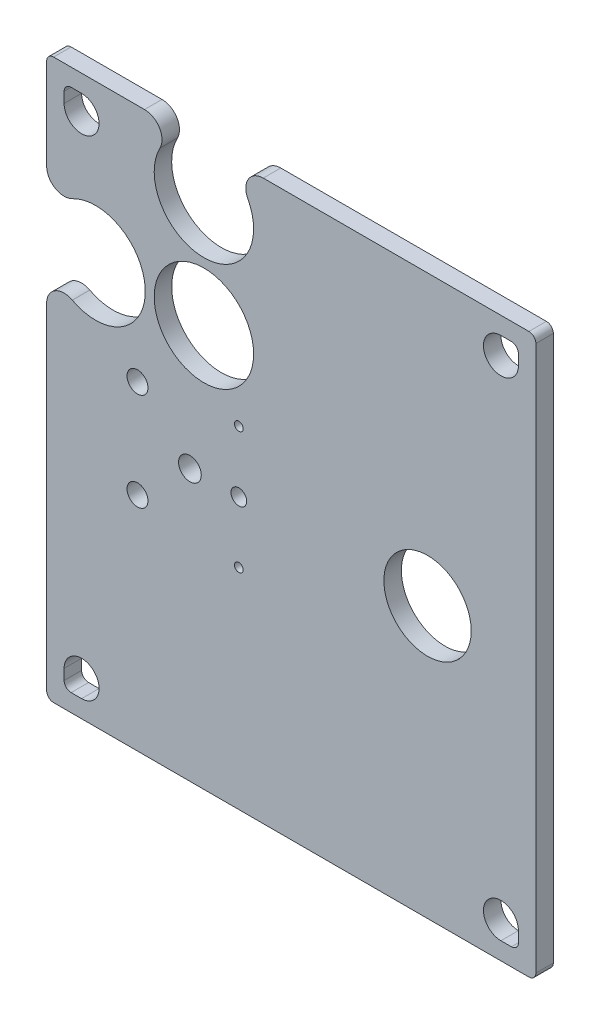
SolidWorks part; units mm, degrees
ref_plane "Front Plane" through (0, 0, 0) normal (0, 0, 1) x (1, 0, 0)
ref_plane "Top Plane" through (0, 0, 0) normal (0, 1, 0) x (1, 0, 0)
ref_plane "Right Plane" through (0, 0, 0) normal (1, 0, 0) x (0, 0, -1)
sketch "Model" plane through (0, 0, 0) normal (0, 0, 1) x (1, 0, 0)
  line L2 (5, 153) -> (5, 150)
  line L3 (10, 155) -> (7, 155)
  line L4 (7, 5) -> (10, 5)
  line L5 (5, 10) -> (5, 7)
  line L6 (135, 7) -> (135, 10)
  line L7 (130, 5) -> (133, 5)
  line L8 (133, 155) -> (130, 155)
  line L9 (135, 150) -> (135, 153)
  line L12 (28.0118, 160) -> (2, 160)
  line L13 (140, 2) -> (140, 158)
  line L14 (2, 0) -> (138, 0)
  line L15 (0, 98.0118) -> (0, 2)
  line L16 (138, 160) -> (61.9882, 160)
  line L17 (0, 158) -> (0, 131.9882)
  circle A0 centre (26, 91.5) radius 3
  circle A1 centre (55, 77.5) radius 2.25
  circle A2 centre (55, 60) radius 1.25
  circle A3 centre (109, 77.5) radius 12.5
  circle A4 centre (55, 95) radius 1.25
  circle A5 centre (26, 63.5) radius 3
  circle A6 centre (41, 77.5) radius 3.25
  circle A7 centre (45, 115) radius 14.225
  arc A9 (7, 155) -> (5, 153) centre (7, 153) ccw
  arc A10 (5, 150) -> (10, 155) centre (10, 150) ccw
  arc A11 (5, 7) -> (7, 5) centre (7, 7) ccw
  arc A12 (10, 5) -> (5, 10) centre (10, 10) ccw
  arc A13 (133, 5) -> (135, 7) centre (133, 7) ccw
  arc A14 (135, 10) -> (130, 5) centre (130, 10) ccw
  arc A15 (135, 153) -> (133, 155) centre (133, 153) ccw
  arc A16 (130, 155) -> (135, 150) centre (130, 150) ccw
  arc A18 (0, 131.9882) -> (7.3407, 127.57) centre (5, 131.9882) ccw
  arc A19 (2, 160) -> (0, 158) centre (2, 158) ccw
  arc A20 (32.43, 152.6593) -> (28.0118, 160) centre (28.0118, 155) ccw
  arc A21 (32.43, 152.6593) -> (57.57, 152.6593) centre (45, 146) ccw
  arc A22 (61.9882, 160) -> (57.57, 152.6593) centre (61.9882, 155) ccw
  arc A23 (140, 158) -> (138, 160) centre (138, 158) ccw
  arc A24 (138, 0) -> (140, 2) centre (138, 2) ccw
  arc A25 (0, 2) -> (2, 0) centre (2, 2) ccw
  arc A26 (7.3407, 102.43) -> (0, 98.0118) centre (5, 98.0118) ccw
  arc A27 (7.3407, 102.43) -> (7.3407, 127.57) centre (14, 115) ccw
extrude "Boss-Extrude1" add sketch "Model" along normal blind 5
